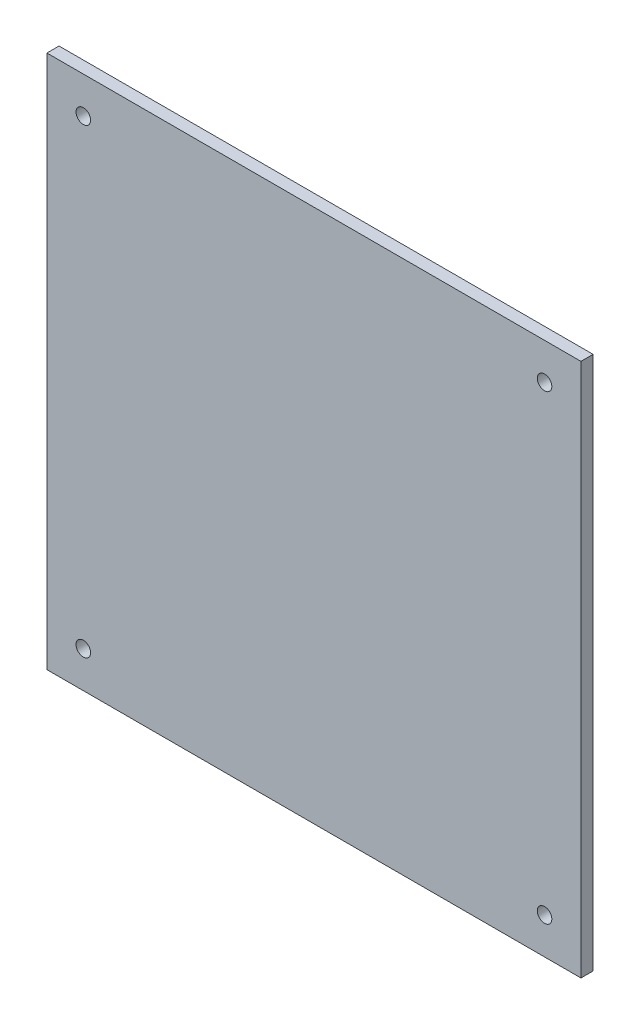
SolidWorks part; units mm, degrees
material "ASTM A36 Steel"
ref_plane "Front Plane" through (0, 0, 0) normal (0, 0, 1) x (1, 0, 0)
ref_plane "Top Plane" through (0, 0, 0) normal (0, 1, 0) x (1, 0, 0)
ref_plane "Right Plane" through (0, 0, 0) normal (1, 0, 0) x (0, 0, -1)
sketch "Sketch1" plane through (0, 0, 0) normal (0, 0, 1) x (1, 0, 0)
  line L1 (162.7083, 214.0972) -> (-277.2917, 214.0972)
  line L2 (162.7083, 214.0972) -> (162.7083, -225.9028)
  line L3 (162.7083, -225.9028) -> (-277.2917, -225.9028)
  line L4 (-277.2917, 214.0972) -> (-277.2917, -225.9028)
  circle A0 centre (132.7083, 184.0972) radius 6
  circle A1 centre (-247.2917, 184.0972) radius 6
  circle A2 centre (-247.2917, -195.9028) radius 6
  circle A3 centre (132.7083, -195.9028) radius 6
  dimension "D3" = 12
  dimension "D6" = 12
  dimension "D7" = 30
  dimension "D8" = 30
  dimension "D9" = 12
  dimension "D10" = 30
  dimension "D11" = 12
  dimension "D1" = 440
  dimension "D2" = 440
  dimension "D4" = 30
  dimension "D5" = 30
extrude "Boss-Extrude1" add sketch "Sketch1" along normal blind 10
